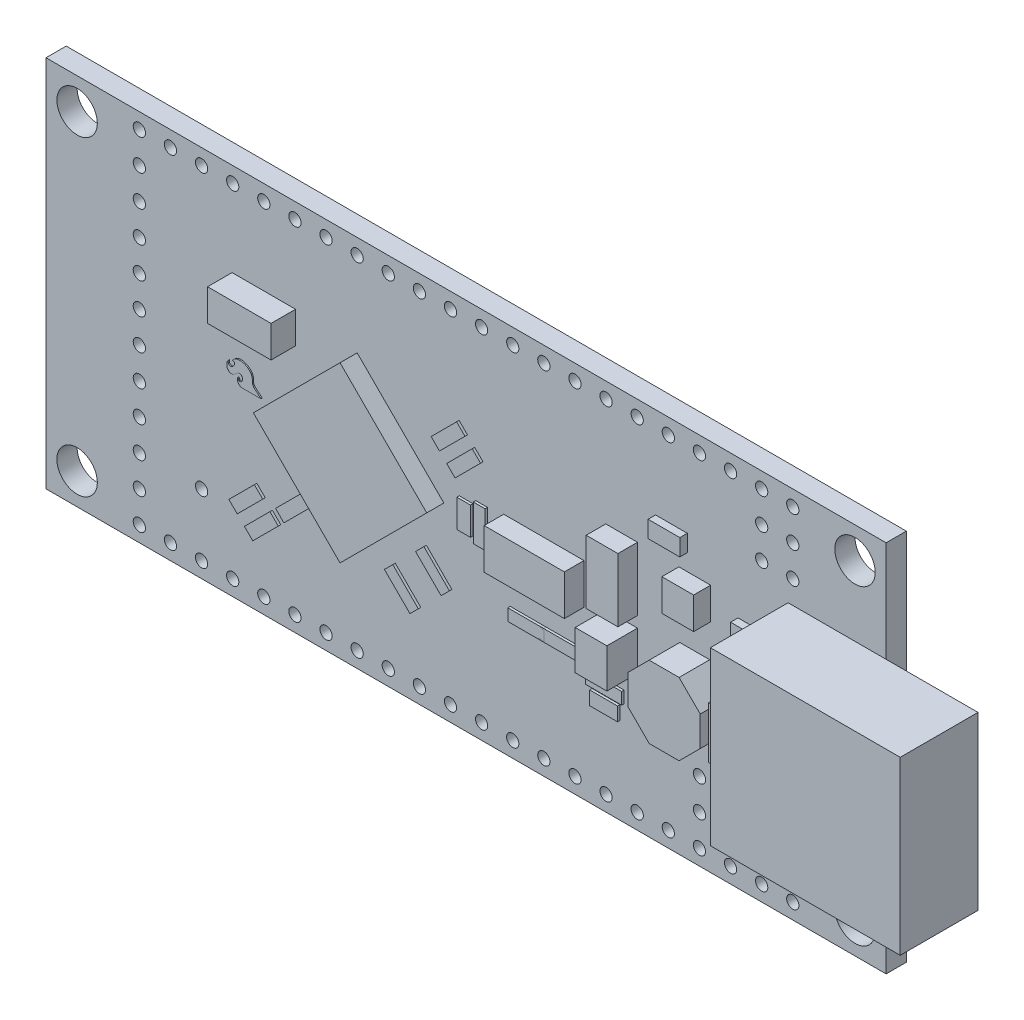
SolidWorks part; units mm, degrees
ref_plane "정면" through (0, 0, 0) normal (0, 0, 1) x (1, 0, 0)
ref_plane "윗면" through (0, 0, 0) normal (0, 1, 0) x (1, 0, 0)
ref_plane "우측면" through (0, 0, 0) normal (1, 0, 0) x (0, 0, -1)
sketch "스케치1" plane through (0, 0, 0) normal (0, 0, 1) x (1, 0, 0)
  line L0 (50.8, 81.28) -> (50.8, 50.8)
  line L1 (50.8, 50.8) -> (119.38, 50.8)
  line L2 (119.38, 50.8) -> (119.38, 81.28)
  line L3 (119.38, 81.28) -> (50.8, 81.28)
extrude "BOARD" add sketch "스케치1" along normal blind 1.65 separate body
ref_plane "평면1" through (0, 0, 3) normal (0, 0, 1) x (1, 0, 0)
sketch "스케치2" plane through (0, 0, 1.65) normal (0, 0, 1) x (1, 0, 0)
  line L0 (81.8495, 62.343) -> (83.933, 60.2595)
  line L1 (83.933, 60.2595) -> (83.2505, 59.577)
  line L2 (83.2505, 59.577) -> (81.167, 61.6605)
  line L3 (81.167, 61.6605) -> (81.8495, 62.343)
extrude "0402-CAP-1" add sketch "스케치2" along normal blind 0.2 separate body
sketch "스케치3" plane through (0, 0, 1.65) normal (0, 0, 1) x (1, 0, 0)
  line L0 (82.437, 70.4195) -> (84.5205, 72.503)
  line L1 (84.5205, 72.503) -> (85.203, 71.8205)
  line L2 (85.203, 71.8205) -> (83.1195, 69.737)
  line L3 (83.1195, 69.737) -> (82.437, 70.4195)
extrude "0402-CAP-2" add sketch "스케치3" along normal blind 0.2 separate body
sketch "스케치4" plane through (0, 0, 1.65) normal (0, 0, 1) x (1, 0, 0)
  line L0 (79.3095, 59.803) -> (81.393, 57.7195)
  line L1 (81.393, 57.7195) -> (80.7105, 57.037)
  line L2 (80.7105, 57.037) -> (78.627, 59.1205)
  line L3 (78.627, 59.1205) -> (79.3095, 59.803)
extrude "0402-CAP-3" add sketch "스케치4" along normal blind 0.2 separate body
sketch "스케치5" plane through (0, 0, 1.65) normal (0, 0, 1) x (1, 0, 0)
  line L0 (72.503, 60.3905) -> (70.4195, 58.307)
  line L1 (70.4195, 58.307) -> (69.737, 58.9895)
  line L2 (69.737, 58.9895) -> (71.8205, 61.073)
  line L3 (71.8205, 61.073) -> (72.503, 60.3905)
sketch "스케치6" plane through (0, 0, 1.65) normal (0, 0, 1) x (1, 0, 0)
  line L0 (83.707, 69.1495) -> (85.7905, 71.233)
  line L1 (85.7905, 71.233) -> (86.473, 70.5505)
  line L2 (86.473, 70.5505) -> (84.3895, 68.467)
  line L3 (84.3895, 68.467) -> (83.707, 69.1495)
extrude "0402-CAP-5" add sketch "스케치6" along normal blind 0.2 separate body
sketch "스케치7" plane through (0, 0, 1.65) normal (0, 0, 1) x (1, 0, 0)
  line L0 (107.2896, 69.9262) -> (109.8804, 69.9262)
  line L1 (109.8804, 69.9262) -> (109.8804, 66.7258)
  line L2 (109.8804, 66.7258) -> (107.2896, 66.7258)
  line L3 (107.2896, 66.7258) -> (107.2896, 69.9262)
extrude "1210-1" add sketch "스케치7" along normal blind 0.6096 separate body
sketch "스케치8" plane through (0, 0, 1.65) normal (0, 0, 1) x (1, 0, 0)
  line L0 (65.9892, 71.0946) -> (71.1708, 71.0946)
  line L1 (71.1708, 71.0946) -> (71.1708, 73.6854)
  line L2 (71.1708, 73.6854) -> (65.9892, 73.6854)
  line L3 (65.9892, 73.6854) -> (65.9892, 71.0946)
extrude "EIA3216-1" add sketch "스케치8" along normal blind 2 separate body
sketch "스케치9" plane through (0, 0, 1.65) normal (0, 0, 1) x (1, 0, 0)
  line L0 (99.0854, 65.9892) -> (99.0854, 71.1708)
  line L1 (99.0854, 71.1708) -> (96.4946, 71.1708)
  line L2 (96.4946, 71.1708) -> (96.4946, 65.9892)
  line L3 (96.4946, 65.9892) -> (99.0854, 65.9892)
extrude "EIA3216-2" add sketch "스케치9" along normal blind 1.6 separate body
sketch "스케치10" plane through (0, 0, 1.65) normal (0, 0, 1) x (1, 0, 0)
  line L0 (99.0854, 61.8998) -> (96.4946, 61.8998)
  line L1 (96.4946, 61.8998) -> (96.4946, 65.1002)
  line L2 (96.4946, 65.1002) -> (99.0854, 65.1002)
  line L3 (99.0854, 65.1002) -> (99.0854, 61.8998)
extrude "1210-2" add sketch "스케치10" along normal blind 2.5 separate body
sketch "스케치11" plane through (0, 0, 1.65) normal (0, 0, 1) x (1, 0, 0)
  line L0 (100.5586, 72.4662) -> (103.1494, 72.4662)
  line L1 (103.1494, 72.4662) -> (103.1494, 73.8378)
  line L2 (103.1494, 73.8378) -> (100.5586, 73.8378)
  line L3 (100.5586, 73.8378) -> (100.5586, 72.4662)
extrude "0805-1" add sketch "스케치11" along normal blind 0.6096 separate body
sketch "스케치12" plane through (0, 0, 1.65) normal (0, 0, 1) x (1, 0, 0)
  line L0 (88.1634, 67.691) -> (94.7166, 67.691)
  line L1 (94.7166, 67.691) -> (94.7166, 64.389)
  line L2 (94.7166, 64.389) -> (88.1634, 64.389)
  line L3 (88.1634, 64.389) -> (88.1634, 67.691)
extrude "SOT223-1" add sketch "스케치12" along normal blind 1.6 separate body
sketch "스케치13" plane through (0, 0, 1.65) normal (0, 0, 1) x (1, 0, 0)
  line L0 (87.63, 80.645) -> (88.265, 81.28)
  line L1 (88.265, 81.28) -> (89.535, 81.28)
  line L2 (89.535, 81.28) -> (90.17, 80.645)
  line L3 (90.17, 80.645) -> (90.805, 81.28)
  line L4 (90.805, 81.28) -> (92.075, 81.28)
  line L5 (92.075, 81.28) -> (92.71, 80.645)
  line L6 (92.71, 80.645) -> (93.345, 81.28)
  line L7 (93.345, 81.28) -> (94.615, 81.28)
  line L8 (94.615, 81.28) -> (95.25, 80.645)
  line L9 (95.25, 80.645) -> (95.885, 81.28)
  line L10 (95.885, 81.28) -> (97.155, 81.28)
  line L11 (97.155, 81.28) -> (97.79, 80.645)
  line L12 (97.79, 80.645) -> (98.425, 81.28)
  line L13 (98.425, 81.28) -> (99.695, 81.28)
  line L14 (99.695, 81.28) -> (100.33, 80.645)
  line L15 (100.33, 80.645) -> (100.965, 81.28)
  line L16 (100.965, 81.28) -> (102.235, 81.28)
  line L17 (102.235, 81.28) -> (102.87, 80.645)
  line L18 (102.87, 80.645) -> (103.505, 81.28)
  line L19 (103.505, 81.28) -> (104.775, 81.28)
  line L20 (104.775, 81.28) -> (105.41, 80.645)
  line L21 (105.41, 80.645) -> (106.045, 81.28)
  line L22 (106.045, 81.28) -> (107.315, 81.28)
  line L23 (107.315, 81.28) -> (107.95, 80.645)
  line L24 (107.95, 80.645) -> (107.95, 79.375)
  line L25 (107.95, 79.375) -> (107.315, 78.74)
  line L26 (107.315, 78.74) -> (106.045, 78.74)
  line L27 (106.045, 78.74) -> (105.41, 79.375)
  line L28 (105.41, 79.375) -> (104.775, 78.74)
  line L29 (104.775, 78.74) -> (103.505, 78.74)
  line L30 (103.505, 78.74) -> (102.87, 79.375)
  line L31 (102.87, 79.375) -> (102.235, 78.74)
  line L32 (102.235, 78.74) -> (100.965, 78.74)
  line L33 (100.965, 78.74) -> (100.33, 79.375)
  line L34 (100.33, 79.375) -> (99.695, 78.74)
  line L35 (99.695, 78.74) -> (98.425, 78.74)
  line L36 (98.425, 78.74) -> (97.79, 79.375)
  line L37 (97.79, 79.375) -> (97.155, 78.74)
  line L38 (97.155, 78.74) -> (95.885, 78.74)
  line L39 (95.885, 78.74) -> (95.25, 79.375)
  line L40 (95.25, 79.375) -> (94.615, 78.74)
  line L41 (94.615, 78.74) -> (93.345, 78.74)
  line L42 (93.345, 78.74) -> (92.71, 79.375)
  line L43 (92.71, 79.375) -> (92.075, 78.74)
  line L44 (92.075, 78.74) -> (90.805, 78.74)
  line L45 (90.805, 78.74) -> (90.17, 79.375)
  line L46 (90.17, 79.375) -> (89.535, 78.74)
  line L47 (89.535, 78.74) -> (88.265, 78.74)
  line L48 (88.265, 78.74) -> (87.63, 79.375)
  line L49 (87.63, 79.375) -> (86.995, 78.74)
  line L50 (86.995, 78.74) -> (85.725, 78.74)
  line L51 (85.725, 78.74) -> (85.09, 79.375)
  line L52 (85.09, 79.375) -> (84.455, 78.74)
  line L53 (84.455, 78.74) -> (83.185, 78.74)
  line L54 (83.185, 78.74) -> (82.55, 79.375)
  line L55 (82.55, 79.375) -> (81.915, 78.74)
  line L56 (81.915, 78.74) -> (80.645, 78.74)
  line L57 (80.645, 78.74) -> (80.01, 79.375)
  line L58 (80.01, 79.375) -> (79.375, 78.74)
  line L59 (79.375, 78.74) -> (78.105, 78.74)
  line L60 (78.105, 78.74) -> (77.47, 79.375)
  line L61 (77.47, 79.375) -> (76.835, 78.74)
  line L62 (76.835, 78.74) -> (75.565, 78.74)
  line L63 (75.565, 78.74) -> (74.93, 79.375)
  line L64 (74.93, 79.375) -> (74.295, 78.74)
  line L65 (74.295, 78.74) -> (73.025, 78.74)
  line L66 (73.025, 78.74) -> (72.39, 79.375)
  line L67 (72.39, 79.375) -> (71.755, 78.74)
  line L68 (71.755, 78.74) -> (70.485, 78.74)
  line L69 (70.485, 78.74) -> (69.85, 79.375)
  line L70 (69.85, 79.375) -> (69.215, 78.74)
  line L71 (69.215, 78.74) -> (67.945, 78.74)
  line L72 (67.945, 78.74) -> (67.31, 79.375)
  line L73 (67.31, 79.375) -> (66.675, 78.74)
  line L74 (66.675, 78.74) -> (65.405, 78.74)
  line L75 (65.405, 78.74) -> (64.77, 79.375)
  line L76 (64.77, 79.375) -> (64.135, 78.74)
  line L77 (64.135, 78.74) -> (62.865, 78.74)
  line L78 (62.865, 78.74) -> (62.23, 79.375)
  line L79 (62.23, 79.375) -> (61.595, 78.74)
  line L80 (61.595, 78.74) -> (60.325, 78.74)
  line L81 (60.325, 78.74) -> (59.69, 79.375)
  line L82 (59.69, 79.375) -> (59.69, 80.645)
  line L83 (59.69, 80.645) -> (60.325, 81.28)
  line L84 (60.325, 81.28) -> (61.595, 81.28)
  line L85 (61.595, 81.28) -> (62.23, 80.645)
  line L86 (62.23, 80.645) -> (62.865, 81.28)
  line L87 (62.865, 81.28) -> (64.135, 81.28)
  line L88 (64.135, 81.28) -> (64.77, 80.645)
  line L89 (64.77, 80.645) -> (65.405, 81.28)
  line L90 (65.405, 81.28) -> (66.675, 81.28)
  line L91 (66.675, 81.28) -> (67.31, 80.645)
  line L92 (67.31, 80.645) -> (67.945, 81.28)
  line L93 (67.945, 81.28) -> (69.215, 81.28)
  line L94 (69.215, 81.28) -> (69.85, 80.645)
  line L95 (69.85, 80.645) -> (70.485, 81.28)
  line L96 (70.485, 81.28) -> (71.755, 81.28)
  line L97 (71.755, 81.28) -> (72.39, 80.645)
  line L98 (72.39, 80.645) -> (73.025, 81.28)
  line L99 (73.025, 81.28) -> (74.295, 81.28)
  line L100 (74.295, 81.28) -> (74.93, 80.645)
  line L101 (74.93, 80.645) -> (75.565, 81.28)
  line L102 (75.565, 81.28) -> (76.835, 81.28)
  line L103 (76.835, 81.28) -> (77.47, 80.645)
  line L104 (77.47, 80.645) -> (78.105, 81.28)
  line L105 (78.105, 81.28) -> (79.375, 81.28)
  line L106 (79.375, 81.28) -> (80.01, 80.645)
  line L107 (80.01, 80.645) -> (80.645, 81.28)
  line L108 (80.645, 81.28) -> (81.915, 81.28)
  line L109 (81.915, 81.28) -> (82.55, 80.645)
  line L110 (82.55, 80.645) -> (83.185, 81.28)
  line L111 (83.185, 81.28) -> (84.455, 81.28)
  line L112 (84.455, 81.28) -> (85.09, 80.645)
  line L113 (85.09, 80.645) -> (85.725, 81.28)
  line L114 (85.725, 81.28) -> (86.995, 81.28)
  line L115 (86.995, 81.28) -> (87.63, 80.645)
sketch "스케치14" plane through (0, 0, 1.65) normal (0, 0, 1) x (1, 0, 0)
  line L0 (107.95, 79.375) -> (107.95, 80.645)
  line L1 (107.95, 80.645) -> (108.585, 81.28)
  line L2 (108.585, 81.28) -> (109.855, 81.28)
  line L3 (109.855, 81.28) -> (110.49, 80.645)
  line L4 (110.49, 80.645) -> (110.49, 79.375)
  line L5 (110.49, 79.375) -> (109.855, 78.74)
  line L6 (109.855, 78.74) -> (110.49, 78.105)
  line L7 (110.49, 78.105) -> (110.49, 76.835)
  line L8 (110.49, 76.835) -> (109.855, 76.2)
  line L9 (109.855, 76.2) -> (110.49, 75.565)
  line L10 (110.49, 75.565) -> (110.49, 74.295)
  line L11 (110.49, 74.295) -> (109.855, 73.66)
  line L12 (109.855, 73.66) -> (108.585, 73.66)
  line L13 (108.585, 73.66) -> (107.95, 74.295)
  line L14 (107.95, 74.295) -> (107.95, 75.565)
  line L15 (107.95, 75.565) -> (108.585, 76.2)
  line L16 (108.585, 76.2) -> (107.95, 76.835)
  line L17 (107.95, 76.835) -> (107.95, 78.105)
  line L18 (107.95, 78.105) -> (108.585, 78.74)
  line L19 (108.585, 78.74) -> (107.95, 79.375)
  point P20 (0, 0)
sketch "스케치15" plane through (0, 0, 1.65) normal (0, 0, 1) x (1, 0, 0)
  line L0 (113.03, 75.565) -> (113.03, 74.295)
  line L1 (113.03, 74.295) -> (112.395, 73.66)
  line L2 (112.395, 73.66) -> (111.125, 73.66)
  line L3 (111.125, 73.66) -> (110.49, 74.295)
  line L4 (110.49, 74.295) -> (110.49, 75.565)
  line L5 (110.49, 75.565) -> (111.125, 76.2)
  line L6 (111.125, 76.2) -> (110.49, 76.835)
  line L7 (110.49, 76.835) -> (110.49, 78.105)
  line L8 (110.49, 78.105) -> (111.125, 78.74)
  line L9 (111.125, 78.74) -> (110.49, 79.375)
  line L10 (110.49, 79.375) -> (110.49, 80.645)
  line L11 (110.49, 80.645) -> (111.125, 81.28)
  line L12 (111.125, 81.28) -> (112.395, 81.28)
  line L13 (112.395, 81.28) -> (113.03, 80.645)
  line L14 (113.03, 80.645) -> (113.03, 79.375)
  line L15 (113.03, 79.375) -> (112.395, 78.74)
  line L16 (112.395, 78.74) -> (113.03, 78.105)
  line L17 (113.03, 78.105) -> (113.03, 76.835)
  line L18 (113.03, 76.835) -> (112.395, 76.2)
  line L19 (112.395, 76.2) -> (113.03, 75.565)
sketch "스케치16" plane through (0, 0, 1.65) normal (0, 0, 1) x (1, 0, 0)
  line L0 (110.49, 56.515) -> (110.49, 57.785)
  line L1 (110.49, 57.785) -> (111.125, 58.42)
  line L2 (111.125, 58.42) -> (112.395, 58.42)
  line L3 (112.395, 58.42) -> (113.03, 57.785)
  line L4 (113.03, 57.785) -> (113.03, 56.515)
  line L5 (113.03, 56.515) -> (112.395, 55.88)
  line L6 (112.395, 55.88) -> (113.03, 55.245)
  line L7 (113.03, 55.245) -> (113.03, 53.975)
  line L8 (113.03, 53.975) -> (112.395, 53.34)
  line L9 (112.395, 53.34) -> (113.03, 52.705)
  line L10 (113.03, 52.705) -> (113.03, 51.435)
  line L11 (113.03, 51.435) -> (112.395, 50.8)
  line L12 (112.395, 50.8) -> (111.125, 50.8)
  line L13 (111.125, 50.8) -> (110.49, 51.435)
  line L14 (110.49, 51.435) -> (110.49, 52.705)
  line L15 (110.49, 52.705) -> (111.125, 53.34)
  line L16 (111.125, 53.34) -> (110.49, 53.975)
  line L17 (110.49, 53.975) -> (110.49, 55.245)
  line L18 (110.49, 55.245) -> (111.125, 55.88)
  line L19 (111.125, 55.88) -> (110.49, 56.515)
sketch "스케치17" plane through (0, 0, 1.65) normal (0, 0, 1) x (1, 0, 0)
  line L0 (105.41, 56.515) -> (105.41, 57.785)
  line L1 (105.41, 57.785) -> (106.045, 58.42)
  line L2 (106.045, 58.42) -> (107.315, 58.42)
  line L3 (107.315, 58.42) -> (107.95, 57.785)
  line L4 (107.95, 57.785) -> (107.95, 56.515)
  line L5 (107.95, 56.515) -> (107.315, 55.88)
  line L6 (107.315, 55.88) -> (107.95, 55.245)
  line L7 (107.95, 55.245) -> (107.95, 53.975)
  line L8 (107.95, 53.975) -> (107.315, 53.34)
  line L9 (107.315, 53.34) -> (107.95, 52.705)
  line L10 (107.95, 52.705) -> (107.95, 51.435)
  line L11 (107.95, 51.435) -> (107.315, 50.8)
  line L12 (107.315, 50.8) -> (106.045, 50.8)
  line L13 (106.045, 50.8) -> (105.41, 51.435)
  line L14 (105.41, 51.435) -> (105.41, 52.705)
  line L15 (105.41, 52.705) -> (106.045, 53.34)
  line L16 (106.045, 53.34) -> (105.41, 53.975)
  line L17 (105.41, 53.975) -> (105.41, 55.245)
  line L18 (105.41, 55.245) -> (106.045, 55.88)
  line L19 (106.045, 55.88) -> (105.41, 56.515)
sketch "스케치18" plane through (0, 0, 1.65) normal (0, 0, 1) x (1, 0, 0)
  line L0 (107.95, 56.515) -> (107.95, 57.785)
  line L1 (107.95, 57.785) -> (108.585, 58.42)
  line L2 (108.585, 58.42) -> (109.855, 58.42)
  line L3 (109.855, 58.42) -> (110.49, 57.785)
  line L4 (110.49, 57.785) -> (110.49, 56.515)
  line L5 (110.49, 56.515) -> (109.855, 55.88)
  line L6 (109.855, 55.88) -> (110.49, 55.245)
  line L7 (110.49, 55.245) -> (110.49, 53.975)
  line L8 (110.49, 53.975) -> (109.855, 53.34)
  line L9 (109.855, 53.34) -> (110.49, 52.705)
  line L10 (110.49, 52.705) -> (110.49, 51.435)
  line L11 (110.49, 51.435) -> (109.855, 50.8)
  line L12 (109.855, 50.8) -> (108.585, 50.8)
  line L13 (108.585, 50.8) -> (107.95, 51.435)
  line L14 (107.95, 51.435) -> (107.95, 52.705)
  line L15 (107.95, 52.705) -> (108.585, 53.34)
  line L16 (108.585, 53.34) -> (107.95, 53.975)
  line L17 (107.95, 53.975) -> (107.95, 55.245)
  line L18 (107.95, 55.245) -> (108.585, 55.88)
  line L19 (108.585, 55.88) -> (107.95, 56.515)
sketch "스케치21" plane through (0, 0, 1.65) normal (0, 0, 1) x (1, 0, 0)
  line L0 (82.55, 52.705) -> (83.185, 53.34)
  line L1 (83.185, 53.34) -> (84.455, 53.34)
  line L2 (84.455, 53.34) -> (85.09, 52.705)
  line L3 (85.09, 52.705) -> (85.725, 53.34)
  line L4 (85.725, 53.34) -> (86.995, 53.34)
  line L5 (86.995, 53.34) -> (87.63, 52.705)
  line L6 (87.63, 52.705) -> (88.265, 53.34)
  line L7 (88.265, 53.34) -> (89.535, 53.34)
  line L8 (89.535, 53.34) -> (90.17, 52.705)
  line L9 (90.17, 52.705) -> (90.805, 53.34)
  line L10 (90.805, 53.34) -> (92.075, 53.34)
  line L11 (92.075, 53.34) -> (92.71, 52.705)
  line L12 (92.71, 52.705) -> (93.345, 53.34)
  line L13 (93.345, 53.34) -> (94.615, 53.34)
  line L14 (94.615, 53.34) -> (95.25, 52.705)
  line L15 (95.25, 52.705) -> (95.885, 53.34)
  line L16 (95.885, 53.34) -> (97.155, 53.34)
  line L17 (97.155, 53.34) -> (97.79, 52.705)
  line L18 (97.79, 52.705) -> (98.425, 53.34)
  line L19 (98.425, 53.34) -> (99.695, 53.34)
  line L20 (99.695, 53.34) -> (100.33, 52.705)
  line L21 (100.33, 52.705) -> (100.965, 53.34)
  line L22 (100.965, 53.34) -> (102.235, 53.34)
  line L23 (102.235, 53.34) -> (102.87, 52.705)
  line L24 (102.87, 52.705) -> (102.87, 51.435)
  line L25 (102.87, 51.435) -> (102.235, 50.8)
  line L26 (102.235, 50.8) -> (100.965, 50.8)
  line L27 (100.965, 50.8) -> (100.33, 51.435)
  line L28 (100.33, 51.435) -> (99.695, 50.8)
  line L29 (99.695, 50.8) -> (98.425, 50.8)
  line L30 (98.425, 50.8) -> (97.79, 51.435)
  line L31 (97.79, 51.435) -> (97.155, 50.8)
  line L32 (97.155, 50.8) -> (95.885, 50.8)
  line L33 (95.885, 50.8) -> (95.25, 51.435)
  line L34 (95.25, 51.435) -> (94.615, 50.8)
  line L35 (94.615, 50.8) -> (93.345, 50.8)
  line L36 (93.345, 50.8) -> (92.71, 51.435)
  line L37 (92.71, 51.435) -> (92.075, 50.8)
  line L38 (92.075, 50.8) -> (90.805, 50.8)
  line L39 (90.805, 50.8) -> (90.17, 51.435)
  line L40 (90.17, 51.435) -> (89.535, 50.8)
  line L41 (89.535, 50.8) -> (88.265, 50.8)
  line L42 (88.265, 50.8) -> (87.63, 51.435)
  line L43 (87.63, 51.435) -> (86.995, 50.8)
  line L44 (86.995, 50.8) -> (85.725, 50.8)
  line L45 (85.725, 50.8) -> (85.09, 51.435)
  line L46 (85.09, 51.435) -> (84.455, 50.8)
  line L47 (84.455, 50.8) -> (83.185, 50.8)
  line L48 (83.185, 50.8) -> (82.55, 51.435)
  line L49 (82.55, 51.435) -> (81.915, 50.8)
  line L50 (81.915, 50.8) -> (80.645, 50.8)
  line L51 (80.645, 50.8) -> (80.01, 51.435)
  line L52 (80.01, 51.435) -> (79.375, 50.8)
  line L53 (79.375, 50.8) -> (78.105, 50.8)
  line L54 (78.105, 50.8) -> (77.47, 51.435)
  line L55 (77.47, 51.435) -> (76.835, 50.8)
  line L56 (76.835, 50.8) -> (75.565, 50.8)
  line L57 (75.565, 50.8) -> (74.93, 51.435)
  line L58 (74.93, 51.435) -> (74.295, 50.8)
  line L59 (74.295, 50.8) -> (73.025, 50.8)
  line L60 (73.025, 50.8) -> (72.39, 51.435)
  line L61 (72.39, 51.435) -> (71.755, 50.8)
  line L62 (71.755, 50.8) -> (70.485, 50.8)
  line L63 (70.485, 50.8) -> (69.85, 51.435)
  line L64 (69.85, 51.435) -> (69.215, 50.8)
  line L65 (69.215, 50.8) -> (67.945, 50.8)
  line L66 (67.945, 50.8) -> (67.31, 51.435)
  line L67 (67.31, 51.435) -> (66.675, 50.8)
  line L68 (66.675, 50.8) -> (65.405, 50.8)
  line L69 (65.405, 50.8) -> (64.77, 51.435)
  line L70 (64.77, 51.435) -> (64.135, 50.8)
  line L71 (64.135, 50.8) -> (62.865, 50.8)
  line L72 (62.865, 50.8) -> (62.23, 51.435)
  line L73 (62.23, 51.435) -> (61.595, 50.8)
  line L74 (61.595, 50.8) -> (60.325, 50.8)
  line L75 (60.325, 50.8) -> (59.69, 51.435)
  line L76 (59.69, 51.435) -> (59.055, 50.8)
  line L77 (59.055, 50.8) -> (57.785, 50.8)
  line L78 (57.785, 50.8) -> (57.15, 51.435)
  line L79 (57.15, 51.435) -> (57.15, 52.705)
  line L80 (57.15, 52.705) -> (57.785, 53.34)
  line L81 (57.785, 53.34) -> (59.055, 53.34)
  line L82 (59.055, 53.34) -> (59.69, 52.705)
  line L83 (59.69, 52.705) -> (60.325, 53.34)
  line L84 (60.325, 53.34) -> (61.595, 53.34)
  line L85 (61.595, 53.34) -> (62.23, 52.705)
  line L86 (62.23, 52.705) -> (62.865, 53.34)
  line L87 (62.865, 53.34) -> (64.135, 53.34)
  line L88 (64.135, 53.34) -> (64.77, 52.705)
  line L89 (64.77, 52.705) -> (65.405, 53.34)
  line L90 (65.405, 53.34) -> (66.675, 53.34)
  line L91 (66.675, 53.34) -> (67.31, 52.705)
  line L92 (67.31, 52.705) -> (67.945, 53.34)
  line L93 (67.945, 53.34) -> (69.215, 53.34)
  line L94 (69.215, 53.34) -> (69.85, 52.705)
  line L95 (69.85, 52.705) -> (70.485, 53.34)
  line L96 (70.485, 53.34) -> (71.755, 53.34)
  line L97 (71.755, 53.34) -> (72.39, 52.705)
  line L98 (72.39, 52.705) -> (73.025, 53.34)
  line L99 (73.025, 53.34) -> (74.295, 53.34)
  line L100 (74.295, 53.34) -> (74.93, 52.705)
  line L101 (74.93, 52.705) -> (75.565, 53.34)
  line L102 (75.565, 53.34) -> (76.835, 53.34)
  line L103 (76.835, 53.34) -> (77.47, 52.705)
  line L104 (77.47, 52.705) -> (78.105, 53.34)
  line L105 (78.105, 53.34) -> (79.375, 53.34)
  line L106 (79.375, 53.34) -> (80.01, 52.705)
  line L107 (80.01, 52.705) -> (80.645, 53.34)
  line L108 (80.645, 53.34) -> (81.915, 53.34)
  line L109 (81.915, 53.34) -> (82.55, 52.705)
sketch "스케치26" plane through (0, 0, 1.65) normal (0, 0, 1) x (1, 0, 0)
  line L0 (59.69, 78.105) -> (59.055, 78.74)
  line L1 (59.055, 78.74) -> (59.69, 79.375)
  line L2 (59.69, 79.375) -> (59.69, 80.645)
  line L3 (59.69, 80.645) -> (59.055, 81.28)
  line L4 (59.055, 81.28) -> (57.785, 81.28)
  line L5 (57.785, 81.28) -> (57.15, 80.645)
  line L6 (57.15, 80.645) -> (57.15, 79.375)
  line L7 (57.15, 79.375) -> (57.785, 78.74)
  line L8 (57.785, 78.74) -> (57.15, 78.105)
  line L9 (57.15, 78.105) -> (57.15, 76.835)
  line L10 (57.15, 76.835) -> (57.785, 76.2)
  line L11 (57.785, 76.2) -> (57.15, 75.565)
  line L12 (57.15, 75.565) -> (57.15, 74.295)
  line L13 (57.15, 74.295) -> (57.785, 73.66)
  line L14 (57.785, 73.66) -> (57.15, 73.025)
  line L15 (57.15, 73.025) -> (57.15, 71.755)
  line L16 (57.15, 71.755) -> (57.785, 71.12)
  line L17 (57.785, 71.12) -> (57.15, 70.485)
  line L18 (57.15, 70.485) -> (57.15, 69.215)
  line L19 (57.15, 69.215) -> (57.785, 68.58)
  line L20 (57.785, 68.58) -> (57.15, 67.945)
  line L21 (57.15, 67.945) -> (57.15, 66.675)
  line L22 (57.15, 66.675) -> (57.785, 66.04)
  line L23 (57.785, 66.04) -> (57.15, 65.405)
  line L24 (57.15, 65.405) -> (57.15, 64.135)
  line L25 (57.15, 64.135) -> (57.785, 63.5)
  line L26 (57.785, 63.5) -> (57.15, 62.865)
  line L27 (57.15, 62.865) -> (57.15, 61.595)
  line L28 (57.15, 61.595) -> (57.785, 60.96)
  line L29 (57.785, 60.96) -> (57.15, 60.325)
  line L30 (57.15, 60.325) -> (57.15, 59.055)
  line L31 (57.15, 59.055) -> (57.785, 58.42)
  line L32 (57.785, 58.42) -> (57.15, 57.785)
  line L33 (57.15, 57.785) -> (57.15, 56.515)
  line L34 (57.15, 56.515) -> (57.785, 55.88)
  line L35 (57.785, 55.88) -> (57.15, 55.245)
  line L36 (57.15, 55.245) -> (57.15, 53.975)
  line L37 (57.15, 53.975) -> (57.785, 53.34)
  line L38 (57.785, 53.34) -> (59.055, 53.34)
  line L39 (59.055, 53.34) -> (59.69, 53.975)
  line L40 (59.69, 53.975) -> (59.69, 55.245)
  line L41 (59.69, 55.245) -> (59.055, 55.88)
  line L42 (59.055, 55.88) -> (59.69, 56.515)
  line L43 (59.69, 56.515) -> (59.69, 57.785)
  line L44 (59.69, 57.785) -> (59.055, 58.42)
  line L45 (59.055, 58.42) -> (59.69, 59.055)
  line L46 (59.69, 59.055) -> (59.69, 60.325)
  line L47 (59.69, 60.325) -> (59.055, 60.96)
  line L48 (59.055, 60.96) -> (59.69, 61.595)
  line L49 (59.69, 61.595) -> (59.69, 62.865)
  line L50 (59.69, 62.865) -> (59.055, 63.5)
  line L51 (59.055, 63.5) -> (59.69, 64.135)
  line L52 (59.69, 64.135) -> (59.69, 65.405)
  line L53 (59.69, 65.405) -> (59.055, 66.04)
  line L54 (59.055, 66.04) -> (59.69, 66.675)
  line L55 (59.69, 66.675) -> (59.69, 67.945)
  line L56 (59.69, 67.945) -> (59.055, 68.58)
  line L57 (59.055, 68.58) -> (59.69, 69.215)
  line L58 (59.69, 69.215) -> (59.69, 70.485)
  line L59 (59.69, 70.485) -> (59.055, 71.12)
  line L60 (59.055, 71.12) -> (59.69, 71.755)
  line L61 (59.69, 71.755) -> (59.69, 73.025)
  line L62 (59.69, 73.025) -> (59.055, 73.66)
  line L63 (59.055, 73.66) -> (59.69, 74.295)
  line L64 (59.69, 74.295) -> (59.69, 75.565)
  line L65 (59.69, 75.565) -> (59.055, 76.2)
  line L66 (59.055, 76.2) -> (59.69, 76.835)
  line L67 (59.69, 76.835) -> (59.69, 78.105)
sketch "스케치27" plane through (0, 0, 1.65) normal (0, 0, 1) x (1, 0, 0)
  line L0 (64.77, 56.515) -> (64.77, 57.785)
  line L1 (64.77, 57.785) -> (64.135, 58.42)
  line L2 (64.135, 58.42) -> (62.865, 58.42)
  line L3 (62.865, 58.42) -> (62.23, 57.785)
  line L4 (62.23, 57.785) -> (62.23, 56.515)
  line L5 (62.23, 56.515) -> (62.865, 55.88)
  line L6 (62.865, 55.88) -> (64.135, 55.88)
  line L7 (64.135, 55.88) -> (64.77, 56.515)
sketch "스케치28" plane through (0, 0, 1.65) normal (0, 0, 1) x (1, 0, 0)
  line L0 (66.548, 66.5988) -> (66.548, 66.548)
  line L1 (66.929, 66.04) -> (68.453, 66.04)
  line L2 (68.453, 66.04) -> (67.8942, 66.5226)
  line L3 (67.7418, 66.802) -> (67.7418, 67.0306)
  line L4 (66.1162, 67.5894) -> (66.1924, 67.5894)
  line L5 (66.2686, 67.3354) -> (66.1924, 67.2338)
  arc A0 (66.548, 66.548) -> (66.548, 66.3448) centre (67.2278, 66.4464) ccw
  arc A1 (66.548, 66.3448) -> (66.7004, 66.1162) centre (66.8935, 66.41) ccw
  arc A2 (66.7004, 66.1162) -> (66.929, 66.04) centre (66.9355, 66.4406) ccw
  arc A3 (67.8942, 66.5226) -> (67.7672, 66.7258) centre (68.3301, 66.9363) cw
  arc A4 (67.7672, 66.7258) -> (67.7418, 66.802) centre (67.9822, 66.8398) cw
  arc A5 (67.7418, 67.0306) -> (67.6402, 67.4116) centre (67.0041, 67.0379) ccw
  arc A6 (67.6402, 67.4116) -> (67.3354, 67.7164) centre (66.7708, 66.847) ccw
  arc A7 (67.3354, 67.7164) -> (66.5988, 67.8942) centre (66.7293, 66.8202) ccw
  arc A8 (66.5988, 67.8942) -> (66.3194, 67.7926) centre (66.6882, 67.2133) ccw
  arc A9 (66.3194, 67.7926) -> (66.1162, 67.5894) centre (66.6958, 67.213) ccw
  arc A10 (66.1924, 67.5894) -> (66.2178, 67.5894) centre (66.2051, 67.542) cw
  arc A11 (66.2178, 67.5894) -> (66.294, 67.5132) centre (66.1273, 67.4227) cw
  arc A12 (66.294, 67.5132) -> (66.294, 67.4878) centre (66.1621, 67.5005) cw
  arc A13 (66.294, 67.4878) -> (66.2686, 67.3354) centre (66.1141, 67.4395) cw
  arc A14 (66.1924, 67.2338) -> (66.1162, 67.1576) centre (65.8994, 67.4506) cw
  arc A15 (66.1162, 67.1576) -> (66.0146, 67.1068) centre (65.905, 67.4529) cw
  arc A16 (66.0146, 67.1068) -> (65.9638, 67.1068) centre (65.9892, 67.2126) cw
  arc A17 (65.9638, 67.1068) -> (65.786, 67.2338) centre (65.9849, 67.3243) cw
  arc A18 (65.786, 67.2338) -> (65.7606, 67.3354) centre (66.094, 67.3648) cw
  arc A19 (65.7606, 67.3354) -> (65.7606, 67.4116) centre (67.2156, 67.3735) cw
  arc A20 (65.7606, 67.4116) -> (65.7098, 67.31) centre (65.9389, 67.2589) ccw
  arc A21 (65.7098, 67.31) -> (65.6844, 67.2846) centre (65.5856, 67.4088) cw
  arc A22 (65.6844, 67.2846) -> (65.6844, 67.2592) centre (65.8163, 67.2719) ccw
  arc A23 (65.6844, 67.2592) -> (65.659, 67.0814) centre (66.2665, 67.0853) ccw
  arc A24 (65.659, 67.0814) -> (65.7098, 66.8274) centre (66.1131, 67.0401) ccw
  arc A25 (65.7098, 66.8274) -> (65.8368, 66.675) centre (66.3521, 67.2335) ccw
  arc A26 (65.8368, 66.675) -> (66.1924, 66.6496) centre (66.0321, 66.907) ccw
  arc A27 (66.1924, 66.6496) -> (66.5226, 66.9036) centre (65.5557, 67.819) ccw
  arc A28 (66.5226, 66.9036) -> (66.8782, 66.8782) centre (66.6905, 66.752) cw
  arc A29 (66.8782, 66.8782) -> (66.929, 66.7004) centre (66.547, 66.6874) cw
  arc A30 (66.929, 66.7004) -> (66.8782, 66.4972) centre (66.6389, 66.665) cw
  arc A31 (66.8782, 66.4972) -> (66.802, 66.421) centre (66.7072, 66.592) cw
  arc A32 (66.802, 66.421) -> (66.6496, 66.421) centre (66.7258, 66.6487) cw
  arc A33 (66.6496, 66.421) -> (66.6242, 66.4464) centre (66.6772, 66.474) cw
  arc A34 (66.6242, 66.4464) -> (66.5734, 66.548) centre (60.7777, 63.5866) ccw
  arc A35 (66.5734, 66.548) -> (66.548, 66.5988) centre (66.6152, 66.6006) cw
extrude "SFE-LOGO-FLAME-1" add sketch "스케치28" along normal blind 0.1 separate body
sketch "스케치29" plane through (0, 0, 1.65) normal (0, 0, 1) x (1, 0, 0)
  line L0 (105.41, 52.705) -> (105.41, 51.435)
  line L1 (105.41, 51.435) -> (104.775, 50.8)
  line L2 (104.775, 50.8) -> (103.505, 50.8)
  line L3 (103.505, 50.8) -> (102.87, 51.435)
  line L4 (102.87, 51.435) -> (102.87, 52.705)
  line L5 (102.87, 52.705) -> (103.505, 53.34)
  line L6 (103.505, 53.34) -> (102.87, 53.975)
  line L7 (102.87, 53.975) -> (102.87, 55.245)
  line L8 (102.87, 55.245) -> (103.505, 55.88)
  line L9 (103.505, 55.88) -> (102.87, 56.515)
  line L10 (102.87, 56.515) -> (102.87, 57.785)
  line L11 (102.87, 57.785) -> (103.505, 58.42)
  line L12 (103.505, 58.42) -> (104.775, 58.42)
  line L13 (104.775, 58.42) -> (105.41, 57.785)
  line L14 (105.41, 57.785) -> (105.41, 56.515)
  line L15 (105.41, 56.515) -> (104.775, 55.88)
  line L16 (104.775, 55.88) -> (105.41, 55.245)
  line L17 (105.41, 55.245) -> (105.41, 53.975)
  line L18 (105.41, 53.975) -> (104.775, 53.34)
  line L19 (104.775, 53.34) -> (105.41, 52.705)
sketch "스케치32" plane through (0, 0, 1.65) normal (0, 0, 1) x (1, 0, 0)
  line L13 (104.9794, 65.8114) -> (102.5386, 65.8114)
  line L14 (102.5386, 65.8114) -> (100.8126, 64.0854)
  line L15 (100.8126, 64.0854) -> (100.8126, 61.6446)
  line L16 (100.8126, 61.6446) -> (102.5386, 59.9186)
  line L17 (102.5386, 59.9186) -> (104.9794, 59.9186)
  line L18 (104.9794, 59.9186) -> (106.7054, 61.6446)
  line L19 (106.7054, 61.6446) -> (106.7054, 64.0854)
  line L20 (106.7054, 64.0854) -> (104.9794, 65.8114)
  circle A1 centre (103.759, 62.865) radius 2.9464 construction
extrude "SRU5028-1" add sketch "스케치32" along normal blind 2.5 separate body
sketch "스케치33" plane through (0, 0, 1.65) normal (0, 0, 1) x (1, 0, 0)
  line L0 (84.5312, 64.897) -> (85.6488, 64.897)
  line L1 (85.6488, 64.897) -> (85.6488, 67.183)
  line L2 (85.6488, 67.183) -> (84.5312, 67.183)
  line L3 (84.5312, 67.183) -> (84.5312, 64.897)
extrude "LED-0603-1" add sketch "스케치33" along normal blind 0.2 separate body
sketch "스케치34" plane through (0, 0, 1.65) normal (0, 0, 1) x (1, 0, 0)
  line L0 (97.663, 57.8612) -> (97.663, 58.9788)
  line L1 (97.663, 58.9788) -> (95.377, 58.9788)
  line L2 (95.377, 58.9788) -> (95.377, 57.8612)
  line L3 (95.377, 57.8612) -> (97.663, 57.8612)
extrude "LED-0603-2" add sketch "스케치34" along normal blind 0.2 separate body
sketch "스케치35" plane through (0, 0, 1.65) normal (0, 0, 1) x (1, 0, 0)
  line L0 (67.197, 56.4495) -> (69.2805, 58.533)
  line L1 (69.2805, 58.533) -> (69.963, 57.8505)
  line L2 (69.963, 57.8505) -> (67.8795, 55.767)
  line L3 (67.8795, 55.767) -> (67.197, 56.4495)
sketch "스케치36" plane through (0, 0, 1.65) normal (0, 0, 1) x (1, 0, 0)
  line L0 (110.2868, 64.7192) -> (106.8832, 64.7192)
  line L1 (106.8832, 64.7192) -> (106.8832, 60.5028)
  line L2 (106.8832, 60.5028) -> (110.2868, 60.5028)
  line L3 (110.2868, 60.5028) -> (110.2868, 64.7192)
extrude "TRIMPOT-3MM-1" add sketch "스케치36" along normal blind 2 separate body
sketch "스케치37" plane through (0, 0, 1.65) normal (0, 0, 1) x (1, 0, 0)
  line L0 (88.6968, 61.4426) -> (91.6432, 61.4426)
  line L1 (91.6432, 61.4426) -> (91.6432, 60.4774)
  line L2 (91.6432, 60.4774) -> (88.6968, 60.4774)
  line L3 (88.6968, 60.4774) -> (88.6968, 61.4426)
extrude "0402-RES-2" add sketch "스케치37" along normal blind 0.2 separate body
sketch "스케치38" plane through (0, 0, 1.65) normal (0, 0, 1) x (1, 0, 0)
  line L0 (94.1832, 60.4774) -> (91.2368, 60.4774)
  line L1 (91.2368, 60.4774) -> (91.2368, 61.4426)
  line L2 (91.2368, 61.4426) -> (94.1832, 61.4426)
  line L3 (94.1832, 61.4426) -> (94.1832, 60.4774)
extrude "0402-RES-3" add sketch "스케치38" along normal blind 0.2 separate body
sketch "스케치39" plane through (0, 0, 1.65) normal (0, 0, 1) x (1, 0, 0)
  line L0 (85.8774, 64.5668) -> (85.8774, 67.5132)
  line L1 (85.8774, 67.5132) -> (86.8426, 67.5132)
  line L2 (86.8426, 67.5132) -> (86.8426, 64.5668)
  line L3 (86.8426, 64.5668) -> (85.8774, 64.5668)
extrude "0402-RES-4" add sketch "스케치39" along normal blind 0.2 separate body
sketch "스케치40" plane through (0, 0, 1.65) normal (0, 0, 1) x (1, 0, 0)
  line L0 (68.693, 59.1205) -> (66.6095, 57.037)
  line L1 (66.6095, 57.037) -> (65.927, 57.7195)
  line L2 (65.927, 57.7195) -> (68.0105, 59.803)
  line L3 (68.0105, 59.803) -> (68.693, 59.1205)
sketch "스케치41" plane through (0, 0, 1.65) normal (0, 0, 1) x (1, 0, 0)
  line L0 (97.9932, 59.2074) -> (95.0468, 59.2074)
  line L1 (95.0468, 59.2074) -> (95.0468, 60.1726)
  line L2 (95.0468, 60.1726) -> (97.9932, 60.1726)
  line L3 (97.9932, 60.1726) -> (97.9932, 59.2074)
extrude "0402-RES-6" add sketch "스케치41" along normal blind 0.2 separate body
sketch "스케치43" plane through (0, 0, 1.65) normal (0, 0, 1) x (1, 0, 0)
  line L0 (76.2, 73.1164) -> (83.2764, 66.04)
  line L1 (83.2764, 66.04) -> (76.2, 58.9636)
  line L2 (76.2, 58.9636) -> (69.1236, 66.04)
  line L3 (69.1236, 66.04) -> (76.2, 73.1164)
extrude "PIC24FXXX_TQFP64-1" add sketch "스케치43" along normal blind 1.397 separate body
sketch "스케치44" plane through (0, 0, 1.65) normal (0, 0, 1) x (1, 0, 0)
  line L0 (105.0544, 71.12) -> (102.4636, 71.12)
  line L1 (102.4636, 71.12) -> (102.4636, 68.5292)
  line L2 (102.4636, 68.5292) -> (105.0544, 68.5292)
  line L3 (105.0544, 68.5292) -> (105.0544, 71.12)
extrude "QFN16-4X4-1" add sketch "스케치44" along normal blind 1.39 separate body
sketch "스케치45" plane through (0, 0, 1.65) normal (0, 0, 1) x (1, 0, 0)
  line L0 (126.88, 73.04) -> (111.38, 73.04)
  line L1 (111.38, 73.04) -> (111.38, 59.04)
  line L2 (111.38, 59.04) -> (126.88, 59.04)
  line L3 (126.88, 59.04) -> (126.88, 73.04)
  line L4 (119.38, 50.8) -> (119.38, 81.28) construction
  line L5 (119.38, 66.04) -> (134.38, 66.04) construction
  point P6 (126.88, 66.04)
  dimension "D1" = 8
  dimension "D2" = 14
  dimension "D3" = 15.5
extrude "USB-A-S-NOSILK-FEMALE-1" add sketch "스케치45" along normal blind 6.35 separate body
sketch "스케치46" plane through (0, 0, 1.65) normal (0, 0, 1) x (1, 0, 0)
  line L2 (112.395, 50.8) -> (111.125, 50.8) construction
  line L3 (113.03, 52.705) -> (113.03, 51.435) construction
  circle A0 centre (111.76, 52.07) radius 0.5
  circle A1 centre (111.76, 54.61) radius 0.5
  circle A2 centre (111.76, 57.15) radius 0.5
  point P2 (111.76, 50.8)
  point P7 (113.03, 52.07)
  dimension "D1" = 3
extrude "컷-돌출1" cut sketch "스케치46" against normal through all
pattern_linear "선형 패턴1" count 4 spacing 2.54 along (-1, 0, 0) of "컷-돌출1"
sketch "스케치47" plane through (0, 0, 1.65) normal (0, 0, 1) x (1, 0, 0)
  circle A0 centre (101.6, 52.07) radius 0.5
  circle A1 centre (104.14, 52.07) radius 0.5 construction
  dimension "D1" = 2.54
extrude "컷-돌출2" cut sketch "스케치47" against normal through all
pattern_linear "선형 패턴2" count 18 spacing 2.54 along (-1, 0, 0) of "컷-돌출2"
sketch "스케치48" plane through (0, 0, 1.65) normal (0, 0, 1) x (1, 0, 0)
  circle A0 centre (58.42, 54.61) radius 0.5
  circle A1 centre (58.42, 52.07) radius 0.5 construction
  dimension "D1" = 2.54
extrude "컷-돌출3" cut sketch "스케치48" against normal through all
pattern_linear "선형 패턴3" count 10 spacing 2.54 along (0, 1, 0) of "컷-돌출3"
sketch "스케치49" plane through (0, 0, 1.65) normal (0, 0, 1) x (1, 0, 0)
  circle A0 centre (58.42, 80.01) radius 0.5
  circle A1 centre (58.42, 77.47) radius 0.5 construction
  dimension "D1" = 2.54
extrude "컷-돌출4" cut sketch "스케치49" against normal through all
pattern_linear "선형 패턴4" count 20 spacing 2.54 along (1, 0, 0) of "컷-돌출4"
pattern_linear "선형 패턴5" count 2 spacing 22.86 along (0, 1, 0) of "컷-돌출1"
pattern_linear "선형 패턴7" count 2 spacing 2.54 along (-1, 0, 0) of "선형 패턴5"
extrude "보스-돌출1" add sketch "스케치35" along normal blind 0.2 separate body
extrude "보스-돌출2" add sketch "스케치40" along normal blind 0.2 separate body
extrude "보스-돌출3" add sketch "스케치5" along normal blind 0.2 separate body
sketch "스케치50" plane through (0, 0, 1.65) normal (0, 0, 1) x (1, 0, 0)
  line L0 (62.23, 57.785) -> (62.23, 56.515) construction
  line L1 (64.135, 58.42) -> (62.865, 58.42) construction
  circle A0 centre (63.5, 57.15) radius 0.5
  point P4 (62.23, 57.15)
  point P7 (63.5, 58.42)
extrude "컷-돌출5" cut sketch "스케치50" against normal through all
sketch "스케치51" plane through (0, 0, 1.65) normal (0, 0, 1) x (1, 0, 0)
  line L0 (50.8, 50.8) -> (119.38, 50.8) construction
  line L1 (50.8, 81.28) -> (50.8, 50.8) construction
  line L2 (119.38, 81.28) -> (50.8, 81.28) construction
  line L3 (119.38, 50.8) -> (119.38, 81.28) construction
  circle A0 centre (53.34, 53.34) radius 1.65
  circle A1 centre (53.34, 78.74) radius 1.65
  circle A2 centre (116.84, 53.34) radius 1.65
  circle A3 centre (116.84, 78.74) radius 1.65
  dimension "D1" = 2.54
  dimension "D3" = 2.54
  dimension "D4" = 2.54
  dimension "D6" = 2.54
  dimension "D2" = 2.54
  dimension "D5" = 2.54
  dimension "D7" = 2.54
extrude "컷-돌출6" cut sketch "스케치51" against normal through all
